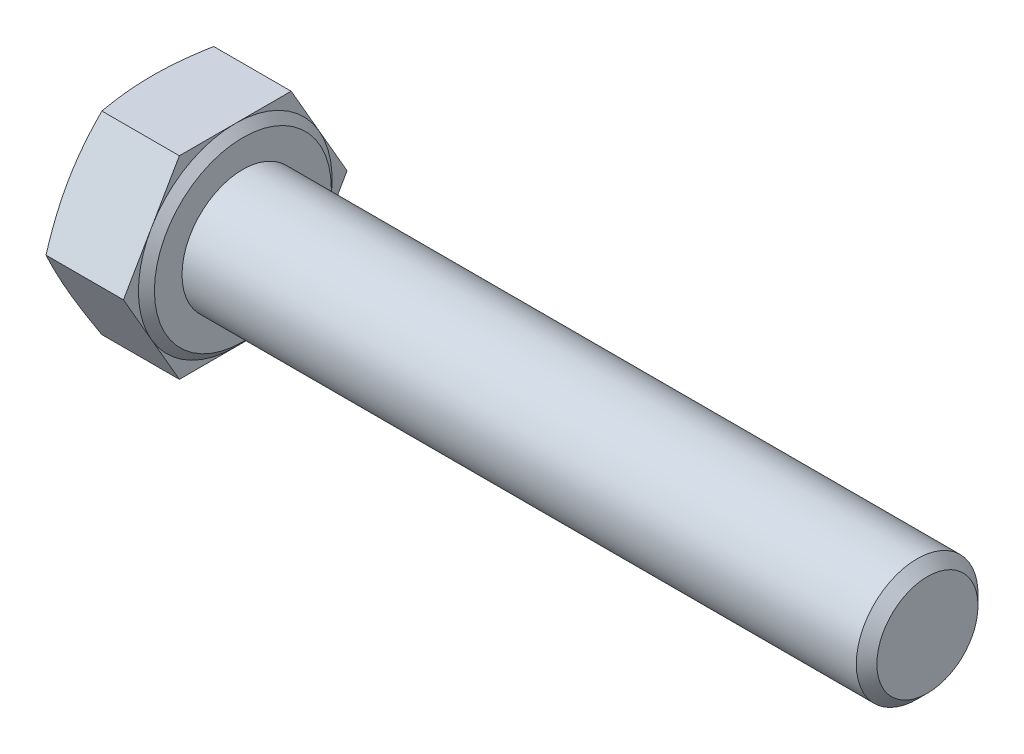
SolidWorks part; units mm, degrees
ref_plane "Front" through (0, 0, 0) normal (0, 0, 1) x (1, 0, 0)
ref_plane "Top" through (0, 0, 0) normal (0, 1, 0) x (1, 0, 0)
ref_plane "Right" through (0, 0, 0) normal (1, 0, 0) x (0, 0, -1)
sketch "Sketch-BaseHead" plane through (0, 0, 0) normal (1, 0, 0) x (0, 0, -1)
  line L1 (7.3497, 0) -> (3.6748, 6.365)
  line L2 (3.6748, 6.365) -> (-3.6748, 6.365)
  line L3 (-3.6748, 6.365) -> (-7.3497, 0)
  line L4 (-7.3497, 0) -> (-3.6748, -6.365)
  line L5 (-3.6748, -6.365) -> (3.6748, -6.365)
  line L6 (3.6748, -6.365) -> (7.3497, 0)
  circle A0 centre (0, 0) radius 6.365 construction
  dimension "s" = 12.73
extrude "BaseHead" add sketch "Sketch-BaseHead" along normal blind 5.45
sketch "Sketch4" plane through (-0.2646, 0, 5.9169) normal (0, 1, 0) x (0, 0, -1)
  line L0 (5.9169, 3.7369) -> (5.9169, -10.4477) construction
  line L2 (13.2666, -0.2646) -> (12.2819, -0.2646)
  line L4 (12.2819, -0.2646) -> (13.2666, -0.623)
  line L6 (13.2666, -0.623) -> (13.2666, -0.2646)
  dimension "D1" = 20
  dimension "D2" = 12.73
revolve "HeadChamfer" cut sketch "Sketch4" angle 360 about L0
sketch "Sketch1" plane through (0, 0, 0) normal (0, 0, 1) x (1, 0, 0)
  line L0 (5.45, 0) -> (5.95, 0)
  line L1 (5.95, 0) -> (5.95, -5.815)
  line L2 (5.95, -5.815) -> (5.45, -6.365)
  line L3 (5.45, -6.365) -> (5.45, 0) construction
  line L4 (0, 0) -> (7.5821, 0) construction
  line L5 (-4.0016, 0) -> (10.1831, 0) construction
  line L6 (5.45, -6.365) -> (0.3584, -6.365) construction
  line L7 (5.45, 0) -> (5.45, -6.365)
  dimension "c" = 0.5
  dimension "D1" = 6.365
  dimension "D2" = 5.815
revolve "Revolve1" add sketch "Sketch1" angle 360 about axis through (-4.0016, 0, 0) along (1, 0, 0)
ref_plane "Plane2" through (28.95, 0, 0) normal (1, 0, 0) x (0, 0, -1)
sketch "Sketch3" plane through (5.95, 0, 0) normal (1, 0, 0) x (0, 0, -1)
  circle A0 centre (0, 0) radius 4
  dimension "d" = 8
extrude "BaseBody" add sketch "Sketch3" along normal blind 45
cosmetic thread "ThreadCosmetic1" [suppressed] parameters "b"=22, "D2"=6.647
fillet "HeadFillet" [suppressed] radius 0.4
chamfer "Chamfer1" distance 0.6765 angle 45 1 edges at (50.95, 0, -4)
sketch "Sketch5" plane through (0, 0, 0) normal (0, 0, 1) x (1, 0, 0)
  line L0 (49.597, 4.6765) -> (50.2735, 4.6765)
  line L1 (50.2735, 4.6765) -> (50.2735, 4)
  line L2 (50.2735, 4) -> (49.9353, 3.4141)
  line L3 (49.9353, 3.4141) -> (49.597, 4)
  line L4 (49.597, 4) -> (49.597, 4.6765)
  line L5 (50.2735, -4) -> (50.2735, 4) construction
  line L6 (50.2735, 4) -> (5.95, 4) construction
  dimension "D1" = 0.6765
revolve "Cut-Revolve10" [suppressed] cut sketch "Sketch5" angle 360
pattern_linear "LPattern10" [suppressed] count 27
equation "\"D1@Sketch1\" = \"s@Sketch-BaseHead\"/ 2"
equation "\"D2@Sketch4\" = \"s@Sketch-BaseHead\""
equation "\"D1@Chamfer1\" =  ( \"d@Sketch3\" - \"D2@ThreadCosmetic1\" ) / 2 "
equation "\"b@ThreadCosmetic1\" = \"l@BaseBody\" - \"lg@Plane2\""
equation "\"D1@Sketch5\" =  (\"d@Sketch3\" - \"D2@ThreadCosmetic1\" )  / 2 "
equation "\"pitch@LPattern10\" = 1.2 * \"D1@Sketch5\""
equation "\"D1@LPattern10\" = \"b@ThreadCosmetic1\" / \"pitch@LPattern10\""
